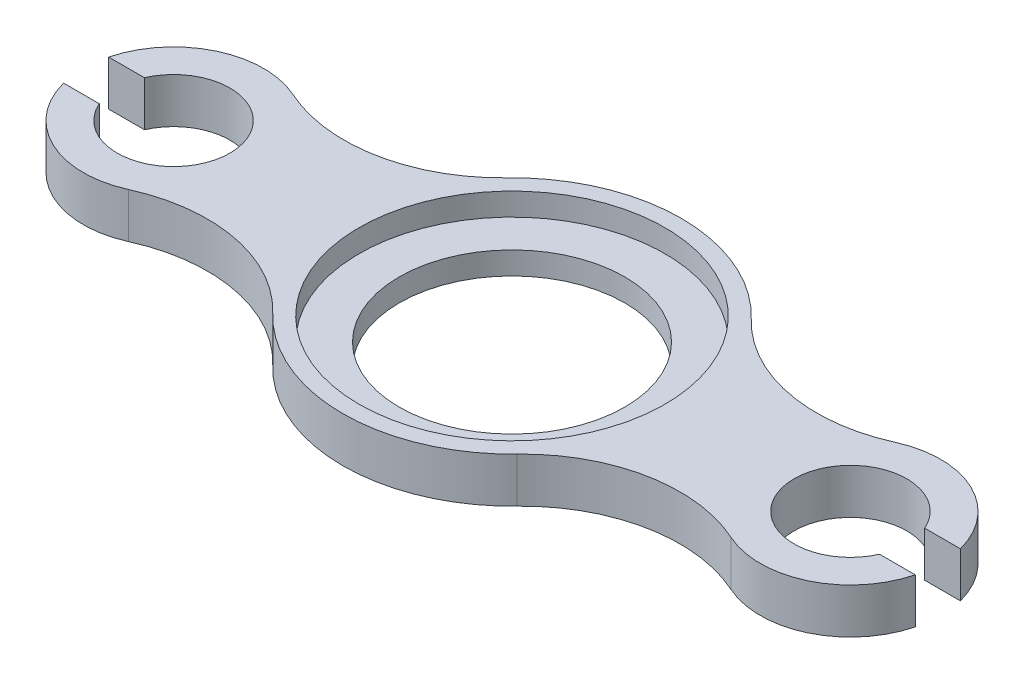
SolidWorks part; units mm, degrees
material "AISI 1020"
ref_plane "Front Plane" through (0, 0, 0) normal (0, 0, 1) x (1, 0, 0)
ref_plane "Top Plane" through (0, 0, 0) normal (0, 1, 0) x (1, 0, 0)
ref_plane "Right Plane" through (0, 0, 0) normal (1, 0, 0) x (0, 0, -1)
sketch "Esquisse1" plane through (0, 0, 0) normal (0, 1, 0) x (1, 0, 0)
  line L0 (194.3996, 0) -> (-194.3996, 0) construction
  line L1 (0, 129.2043) -> (0, -115.2693) construction
  line L2 (172.9129, 10) -> (188.7298, 10)
  line L3 (172.9129, -10) -> (188.7298, -10)
  line L5 (-172.9129, 10) -> (-188.7298, 10)
  line L6 (-172.9129, -10) -> (-188.7298, -10)
  arc A0 (-54.181, -51.8596) -> (54.181, -51.8596) centre (0, 0) ccw
  arc A1 (-188.7298, -10) -> (-133.5455, -36.4589) centre (-150, 0) ccw
  arc A2 (-172.9129, -10) -> (-172.9129, 10) centre (-150, 0) ccw
  circle A3 centre (0, 0) radius 50
  arc A4 (-133.5455, 36.4589) -> (-54.181, 51.8596) centre (-104.75, 100.2618) ccw
  arc A5 (-54.181, -51.8596) -> (-133.5455, -36.4589) centre (-104.75, -100.2618) ccw
  arc A6 (-133.5455, 36.4589) -> (-188.7298, 10) centre (-150, 0) ccw
  arc A7 (133.5455, 36.4589) -> (54.181, 51.8596) centre (104.75, 100.2618) cw
  arc A8 (54.181, -51.8596) -> (133.5455, -36.4589) centre (104.75, -100.2618) cw
  arc A9 (188.7298, -10) -> (133.5455, -36.4589) centre (150, 0) cw
  arc A10 (172.9129, -10) -> (172.9129, 10) centre (150, 0) cw
  arc A11 (133.5455, 36.4589) -> (188.7298, 10) centre (150, 0) cw
  arc A12 (54.181, 51.8596) -> (-54.181, 51.8596) centre (0, 0) ccw
  dimension "D1" = 75
  dimension "D2" = 40
  dimension "D3" = 50
  dimension "D5" = 100
  dimension "D6" = 70
  dimension "D7" = 70
  dimension "D4" = 150
  dimension "D8" = 20
  dimension "D9" = 15.817
extrude "Boss.-Extru.1" add sketch "Esquisse1" along normal blind 20
sketch "Esquisse2" plane through (0, 20, 0) normal (0, 1, 0) x (1, 0, 0)
  circle A0 centre (0, 0) radius 67.8
  dimension "D1" = 135.6
extrude "Enlèv. mat.-Extru.1" cut sketch "Esquisse2" against normal blind 10
